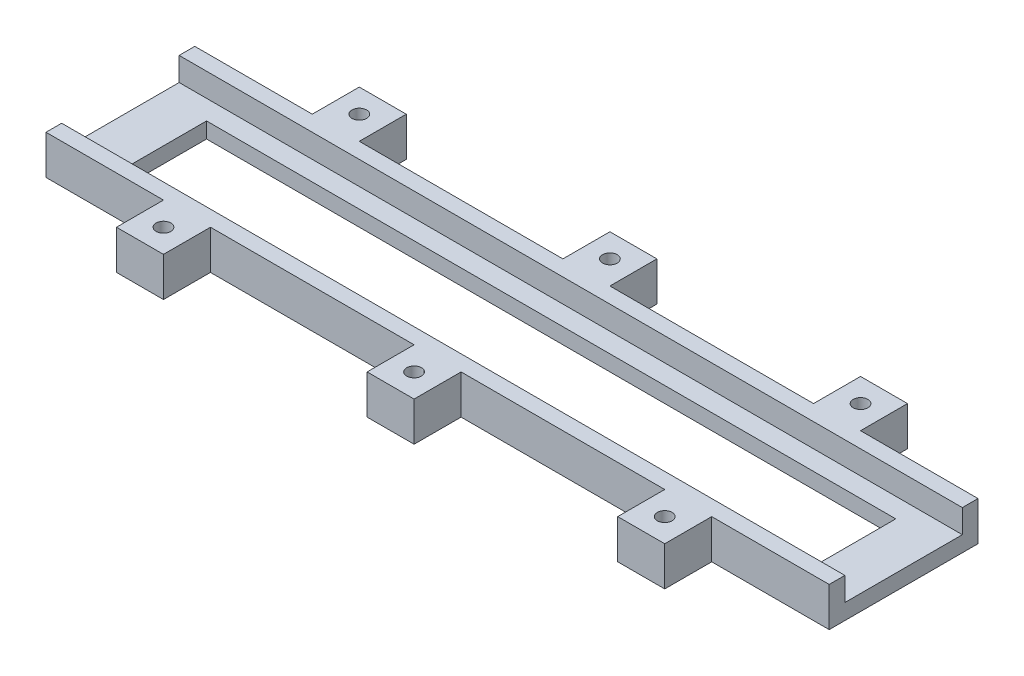
SolidWorks part; units mm, degrees
ref_plane "Front Plane" through (0, 0, 0) normal (0, 0, 1) x (1, 0, 0)
ref_plane "Top Plane" through (0, 0, 0) normal (0, 1, 0) x (1, 0, 0)
ref_plane "Right Plane" through (0, 0, 0) normal (1, 0, 0) x (0, 0, -1)
sketch "Sketch1" plane through (0, 0, 0) normal (0, 1, 0) x (1, 0, 0)
  line L1 (0, 0) -> (160, 0)
  line L2 (0, 0) -> (0, -30.4)
  line L3 (0, -30.4) -> (160, -30.4)
  line L4 (160, 0) -> (160, -30.4)
  dimension "D1" = 30.4
  dimension "D2" = 160
extrude "Boss-Extrude1" add sketch "Sketch1" along normal blind 3.2
sketch "Sketch2" plane through (0, 3.2, 0) normal (0, 1, 0) x (1, 0, 0)
  line L0 (160, -30.4) -> (160, 0) construction
  line L1 (0, -30.4) -> (160, -30.4)
  line L2 (0, -30.4) -> (0, -27.2)
  line L3 (0, -27.2) -> (160, -27.2)
  line L4 (160, -30.4) -> (160, -27.2)
  line L5 (0, 0) -> (0, -30.4) construction
  line L6 (160, 0) -> (0, 0)
  line L7 (160, 0) -> (160, -3.2)
  line L8 (160, -3.2) -> (0, -3.2)
  line L9 (0, 0) -> (0, -3.2)
  dimension "D1" = 3.2
  dimension "D2" = 3.2
extrude "Boss-Extrude2" add sketch "Sketch2" along normal blind 4.8
sketch "Sketch3" plane through (0, 3.2, 0) normal (0, 1, 0) x (1, 0, 0)
  line L0 (0, -3.2) -> (0, -27.2) construction
  line L1 (9.6, -7.2) -> (150.4, -7.2)
  line L2 (9.6, -7.2) -> (9.6, -23.2)
  line L3 (9.6, -23.2) -> (150.4, -23.2)
  line L4 (150.4, -7.2) -> (150.4, -23.2)
  line L5 (160, -27.2) -> (160, -3.2) construction
  line L6 (0, -3.2) -> (160, -3.2) construction
  line L7 (160, -27.2) -> (0, -27.2) construction
  dimension "D1" = 9.6
  dimension "D2" = 9.6
  dimension "D3" = 4
  dimension "D4" = 4
extrude "Cut-Extrude1" cut sketch "Sketch3" against normal through all
sketch "Sketch4" plane through (0, 8, 0) normal (0, 1, 0) x (1, 0, 0)
  line L0 (0, -30.4) -> (160, -30.4) construction
  line L1 (24, -30.4) -> (33.6, -30.4)
  line L2 (24, -30.4) -> (24, -40)
  line L3 (24, -40) -> (33.6, -40)
  line L4 (33.6, -30.4) -> (33.6, -40)
  line L5 (75.2, -40) -> (84.8, -40)
  line L6 (84.8, -30.4) -> (84.8, -40)
  line L7 (75.2, -30.4) -> (84.8, -30.4)
  line L8 (75.2, -30.4) -> (75.2, -40)
  line L9 (126.4, -40) -> (136, -40)
  line L10 (136, -30.4) -> (136, -40)
  line L11 (126.4, -30.4) -> (136, -30.4)
  line L12 (126.4, -30.4) -> (126.4, -40)
  line L13 (75.2, 0) -> (84.8, 0)
  line L14 (84.8, 9.6) -> (84.8, 0)
  line L15 (75.2, 9.6) -> (84.8, 9.6)
  line L16 (75.2, 9.6) -> (75.2, 0)
  line L17 (126.4, 0) -> (136, 0)
  line L18 (136, 9.6) -> (136, 0)
  line L19 (126.4, 9.6) -> (136, 9.6)
  line L20 (126.4, 9.6) -> (126.4, 0)
  line L21 (24, 0) -> (33.6, 0)
  line L22 (33.6, 9.6) -> (33.6, 0)
  line L23 (24, 9.6) -> (33.6, 9.6)
  line L24 (24, 9.6) -> (24, 0)
  circle A0 centre (28.8, -35.2) radius 1.5
  circle A1 centre (80, -35.2) radius 1.5
  circle A2 centre (131.2, -35.2) radius 1.5
  circle A3 centre (80, 4.8) radius 1.5
  circle A4 centre (131.2, 4.8) radius 1.5
  circle A5 centre (28.8, 4.8) radius 1.5
  dimension "D1" = 9.6
  dimension "D2" = 9.6
  dimension "D6" = 3
  dimension "D3" = 24
  dimension "D4" = 3
  dimension "D5" = 2
extrude "Boss-Extrude3" add sketch "Sketch4" against normal blind 8
equation "\"滑动-垂直孔\" = 0.6"
equation "\"滑动-水平孔\" = 0.3"
equation "\"松动-垂直孔\" = 0.3"
equation "\"松动-水平孔\" = 0.1"
equation "\"正常-垂直孔\" = 0.15"
equation "\"正常-水平孔\" = 0"
equation "\"紧缩-垂直孔\" = 0"
equation "\"紧缩-水平孔\" = -0.1"
equation "\"喷嘴宽度\" = \"_喷嘴物理宽度\" * \"_喷嘴宽度系数\""
equation "\"D1@Sketch1\"=\"喷嘴宽度\"*4*2 + \"喷嘴宽度\"*30"
equation "\"D1@Boss-Extrude1\"=\"喷嘴厚度\"*4"
equation "\"D1@Sketch2\"=\"喷嘴宽度\"*4"
equation "\"D2@Sketch2\"=\"D1@Sketch2\""
equation "\"D1@Boss-Extrude2\"=\"喷嘴厚度\"*5 + \"喷嘴厚度\"*1"
equation "\"喷嘴厚度\" = \"_物理厚度\" * \"_物理厚度系数\""
equation "\"D2@Sketch1\"=\"喷嘴宽度\"*200"
equation "\"D1@Sketch3\"=\"喷嘴宽度\"*12"
equation "\"D2@Sketch3\"=\"D1@Sketch3\""
equation "\"D3@Sketch3\"=\"喷嘴宽度\"*5"
equation "\"D4@Sketch3\"=\"D3@Sketch3\""
equation "\"D1@Sketch4\"=\"喷嘴宽度\"*12"
equation "\"D2@Sketch4\"=\"D1@Sketch4\""
equation "\"D3@Sketch4\"=\"喷嘴宽度\"*30"
equation "\"D1@Boss-Extrude3\"=\"喷嘴厚度\"*10"
equation "\"D6@Sketch4\"=\"紧缩-垂直孔\"+3"
equation "\"喷嘴物理宽度\"= 0.8"
equation "\"喷嘴宽度系数\"= 1"
equation "\"物理厚度\"= 0.4"
equation "\"物理厚度系数\"= 2"
